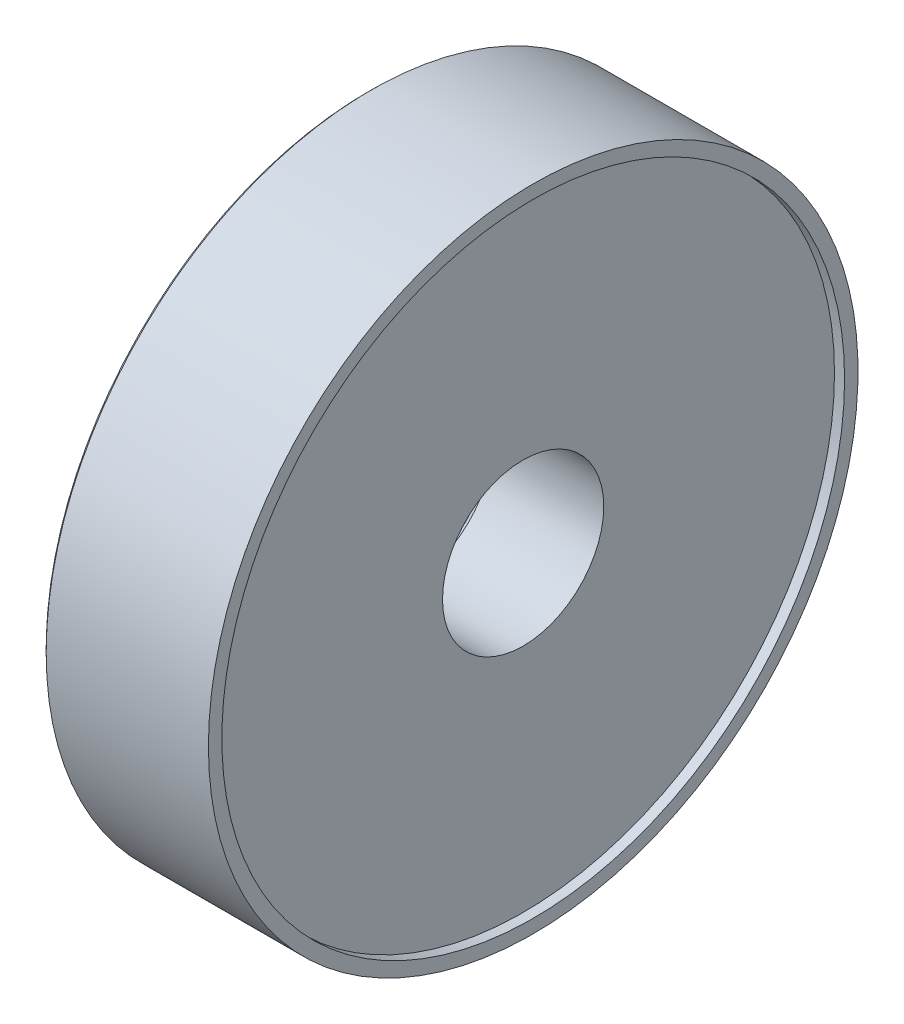
SolidWorks part; units mm, degrees
ref_plane "Front Plane" through (0, 0, 0) normal (0, 0, 1) x (1, 0, 0)
ref_plane "Top Plane" through (0, 0, 0) normal (0, 1, 0) x (1, 0, 0)
ref_plane "Right Plane" through (0, 0, 0) normal (1, 0, 0) x (0, 0, -1)
sketch "Sketch1" plane through (0, 0, 0) normal (1, 0, 0) x (0, 0, -1)
  circle A0 centre (0, 0) radius 48.35
  dimension "D1" = 96.7
extrude "Boss-Extrude1" add sketch "Sketch1" along normal mid plane 25.15
sketch "Sketch2" plane through (-12.575, 0, 0) normal (-1, 0, 0) x (0, 0, 1)
  line L0 (0, 0) -> (0, 43.35) construction
  circle A0 centre (0, 0) radius 43.35 construction
  circle A1 centre (0, 43.35) radius 1.25
  dimension "D1" = 86.7
  dimension "D2" = 2.5
extrude "Cut-Extrude1" cut sketch "Sketch2" against normal blind 3
chamfer "Chamfer1" distance 0.5 angle 45 1 edges at (-12.575, 43.35, 1.25)
pattern_circular "CirPattern1" count 6 over 360 about axis through (0, 0, 0) along (1, 0, 0) of "Cut-Extrude1", "Chamfer1"
sketch "Sketch3" plane through (-12.575, 0, 0) normal (-1, 0, 0) x (0, 0, 1)
  circle A0 centre (0, 0) radius 12
  dimension "D1" = 24
extrude "Cut-Extrude2" cut sketch "Sketch3" against normal up to surface (25.15 mm away) up to face at (12.575, 0, -48.35)
chamfer "Chamfer2" distance 1.25 angle 45 1 edges at (-12.575, 0, 12)
chamfer "Chamfer3" distance 0.5 angle 45 1 edges at (-12.575, 0, -48.35)
sketch "Sketch4" plane through (-12.575, 0, 0) normal (-1, 0, 0) x (0, 0, 1)
  circle A0 centre (0, 0) radius 28.25
  dimension "D1" = 56.5
extrude "Cut-Extrude3" cut sketch "Sketch4" against normal blind 5.35
sketch "Sketch5" plane through (-7.225, 0, 0) normal (-1, 0, 0) x (0, 0, 1)
  line L1 (-15.5, -15.5) -> (15.5, -15.5) construction
  line L2 (-15.5, -15.5) -> (-15.5, 15.5) construction
  line L3 (-15.5, 15.5) -> (15.5, 15.5) construction
  line L4 (15.5, -15.5) -> (15.5, 15.5) construction
  line L5 (-15.5, -15.5) -> (15.5, 15.5) construction
  line L6 (-15.5, 15.5) -> (15.5, -15.5) construction
  circle A0 centre (-15.5, 15.5) radius 3.5
  circle A1 centre (15.5, 15.5) radius 3.5
  circle A2 centre (15.5, -15.5) radius 3.5
  circle A3 centre (-15.5, -15.5) radius 3.5
  point P0 (0, 0)
  dimension "D2" = 7
  dimension "D1" = 31
extrude "Boss-Extrude2" add sketch "Sketch5" along normal blind 3.85
sketch "Sketch6" plane through (-11.075, 0, 0) normal (-1, 0, 0) x (0, 0, 1)
  circle A0 centre (-15.5, 15.5) radius 1.25
  circle A1 centre (15.5, 15.5) radius 1.25
  circle A2 centre (15.5, -15.5) radius 1.25
  circle A3 centre (-15.5, -15.5) radius 1.25
  dimension "D1" = 2.5
extrude "Cut-Extrude4" cut sketch "Sketch6" against normal blind 5.85
sketch "Sketch7" plane through (12.575, 0, 0) normal (1, 0, 0) x (0, 0, -1)
  circle A0 centre (0, 0) radius 46.35
  circle A1 centre (0, 0) radius 48.35 construction
  circle A4 centre (0, 0) radius 30.75
  circle A5 centre (0, 0) radius 30.75 construction
  point P2 (0, 0)
  dimension "D1" = 2
  dimension "D2" = 2.5
extrude "Cut-Extrude5" cut sketch "Sketch7" against normal blind 2
sketch "Sketch8" plane through (12.575, 0, 0) normal (1, 0, 0) x (0, 0, -1)
  circle A0 centre (0, 0) radius 46.35 construction
  circle A1 centre (0, 0) radius 48.35
  circle A2 centre (0, 0) radius 48.35
  circle A3 centre (0, 0) radius 46.35
  dimension "D1" = 0
extrude "Cut-Extrude6" cut sketch "Sketch8" against normal blind 0.5
chamfer "Chamfer4" distance 1.25 angle 45 1 edges at (-7.225, 0, 12)
